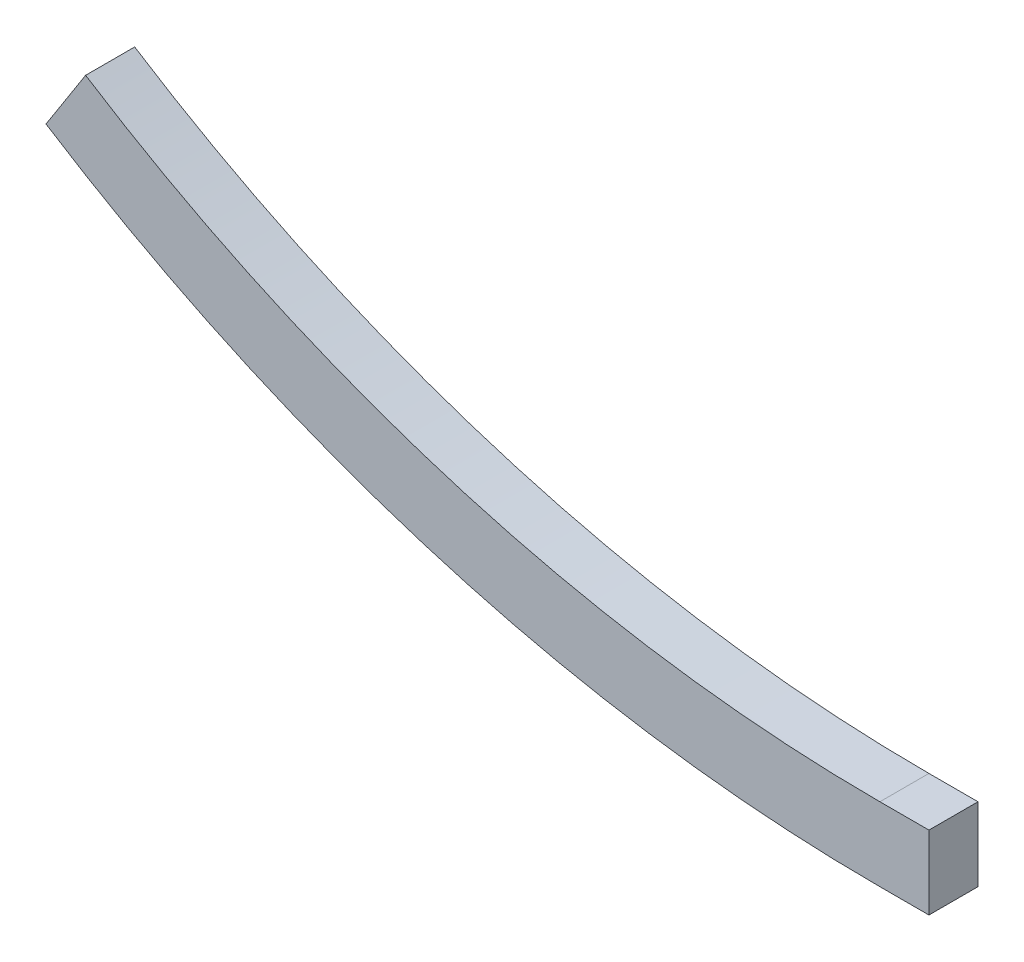
SolidWorks part; units mm, degrees
material "ABS"
ref_plane "Plan de face" through (0, 0, 0) normal (0, 0, 1) x (1, 0, 0)
ref_plane "Plan de dessus" through (0, 0, 0) normal (0, 1, 0) x (1, 0, 0)
ref_plane "Plan de droite" through (0, 0, 0) normal (1, 0, 0) x (0, 0, -1)
sketch "Esquisse2" plane through (0, 0, 0) normal (0, 0, 1) x (1, 0, 0)
  line L2 (-240.4858, 113.4241) -> (0, 0) construction
  line L3 (-234.0871, 126.9909) -> (7.2773, 13.1524) construction
  line L4 (0, 0) -> (8.0755, 12.6407)
  line L5 (170, -34.6539) -> (180, -34.6539)
  line L6 (180, -34.6539) -> (180, -49.6539)
  line L7 (180, -49.6539) -> (170, -49.6539)
  arc A0 (8.0755, 12.6407) -> (170, -34.6539) centre (169.9554, 266.0348) ccw
  arc A1 (0, 0) -> (170, -49.6539) centre (169.9554, 266.0348) ccw
  arc A2 (0, 0) -> (170.0022, -49.6539) centre (169.9554, 266.0348) ccw construction
  arc A4 (7.2773, 13.1524) -> (170, -34.6539) centre (169.9554, 266.0348) ccw construction
  dimension "D2" = 180
  dimension "D3" = 170
  dimension "D1" = 15
extrude "Boss.-Extru.1" add sketch "Esquisse2" along normal blind 10
